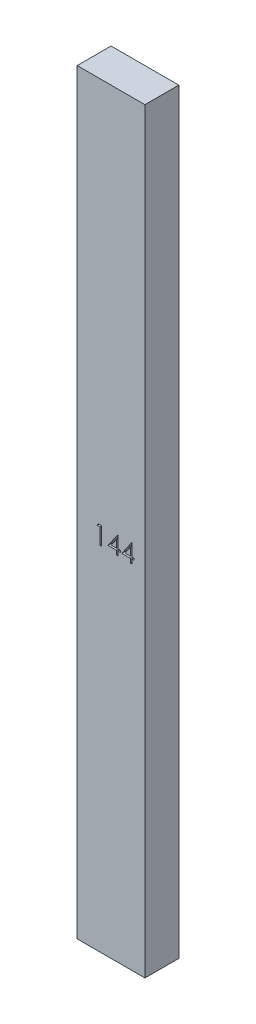
SolidWorks part; units mm, degrees
material "Acrylic (Medium-high impact)"
ref_plane "Front Plane" through (0, 0, 0) normal (0, 0, 1) x (1, 0, 0)
ref_plane "Top Plane" through (0, 0, 0) normal (0, 1, 0) x (1, 0, 0)
ref_plane "Right Plane" through (0, 0, 0) normal (1, 0, 0) x (0, 0, -1)
sketch "Sketch1" plane through (0, 0, 0) normal (0, 1, 0) x (1, 0, 0)
  line L1 (-6, 3) -> (6, 3)
  line L2 (-6, 3) -> (-6, -3)
  line L3 (-6, -3) -> (6, -3)
  line L4 (6, 3) -> (6, -3)
  line L5 (-6, 3) -> (6, -3) construction
  line L6 (-6, -3) -> (6, 3) construction
  point P0 (0, 0)
  dimension "D1" = 6
  dimension "D2" = 12
extrude "Boss-Extrude1" add sketch "Sketch1" along normal blind 134
sketch "Sketch2" plane through (0, 0, 3) normal (0, 0, 1) x (1, 0, 0)
  text T0 "144"
extrude "Cut-Extrude1" cut sketch "Sketch2" against normal blind 1
ref_plane "Plane1" through (-6, 134, 3) normal (1, 0, 0) x (0, 0, -1)
